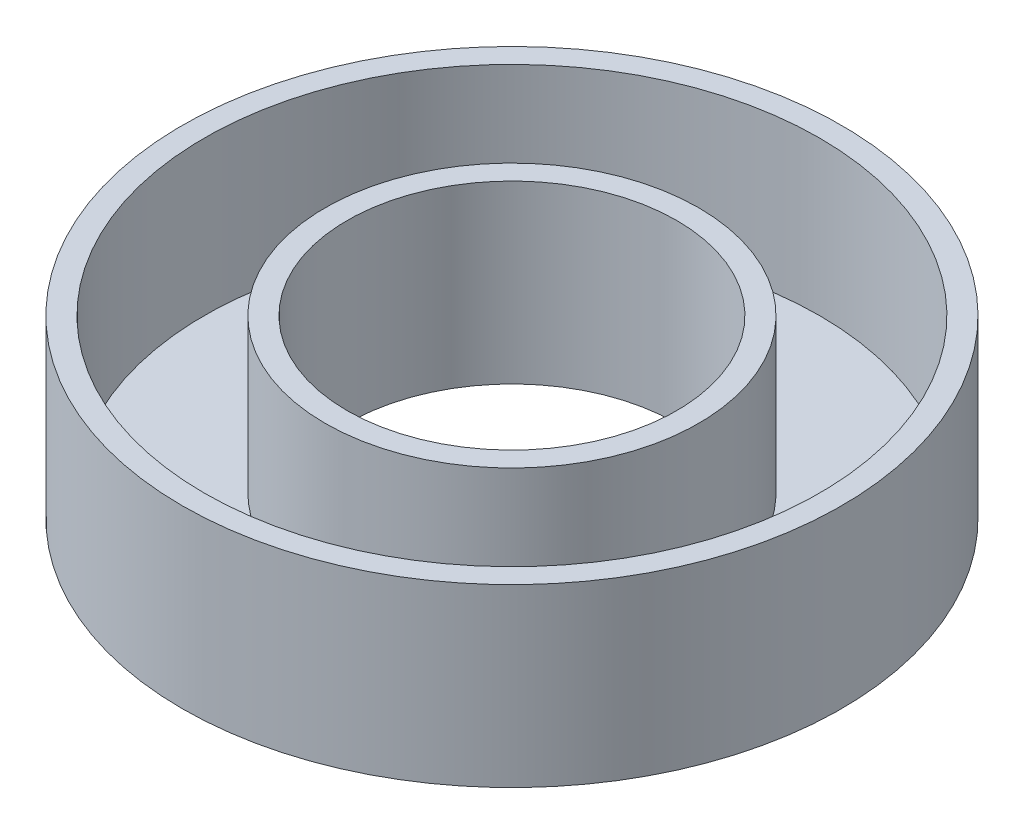
SolidWorks part; units mm, degrees
material "VITON"
ref_plane "Front Plane" through (0, 0, 0) normal (0, 0, 1) x (1, 0, 0)
ref_plane "Top Plane" through (0, 0, 0) normal (0, 1, 0) x (1, 0, 0)
ref_plane "Right Plane" through (0, 0, 0) normal (1, 0, 0) x (0, 0, -1)
sketch "Sketch1" plane through (0, 0, 0) normal (0, 1, 0) x (1, 0, 0)
  circle A0 centre (0, 0) radius 15
  dimension "D1" = 30
extrude "main extrusion" add sketch "Sketch1" along normal blind 8 contours A0
sketch "Sketch2" plane through (0, 8, 0) normal (0, 1, 0) x (1, 0, 0)
  circle A0 centre (0, 0) radius 7.5
  dimension "D1" = 15
extrude "ID bore" cut sketch "Sketch2" against normal blind 20
sketch "Sketch3" plane through (0, 8, 0) normal (0, 1, 0) x (1, 0, 0)
  circle A0 centre (0, 0) radius 14
  circle A1 centre (0, 0) radius 8.5
  dimension "D1" = 17
  dimension "D2" = 28
extrude "seal recess" cut sketch "Sketch3" against normal blind 7
equation "\"D1@Sketch1\" = \"big seal OD\""
equation "\"D1@main extrusion\"=\"big seal depth\""
equation "\"D1@Sketch2\" = \"big seal ID\""
equation "\"motor mount pattern diameter\"= 30mm"
equation "\"D2@Sketch3\" = \"big seal OD\" - 2mm"
equation "\"D1@Sketch3\" = \"big seal ID\" + 2mm"
equation "\"D1@seal recess\" = \"big seal depth\" - 1mm"
equation "\"bearing OD\" = 30mm"
equation "\"bearing outer race thickness\"= 1mm"
equation "\"bearing ID\"= 10mm"
equation "\"bearing depth\"= 9mm"
equation "\"bearing inner race thickness\"= 1mm"
equation "\"small seal OD\" = 20mm"
equation "\"small seal ID\"= 8mm"
equation "\"small seal depth\" = 6mm"
equation "\"big seal OD\" = 30mm"
equation "\"big seal ID\"= 15mm"
equation "\"big seal depth\"= 8mm"
